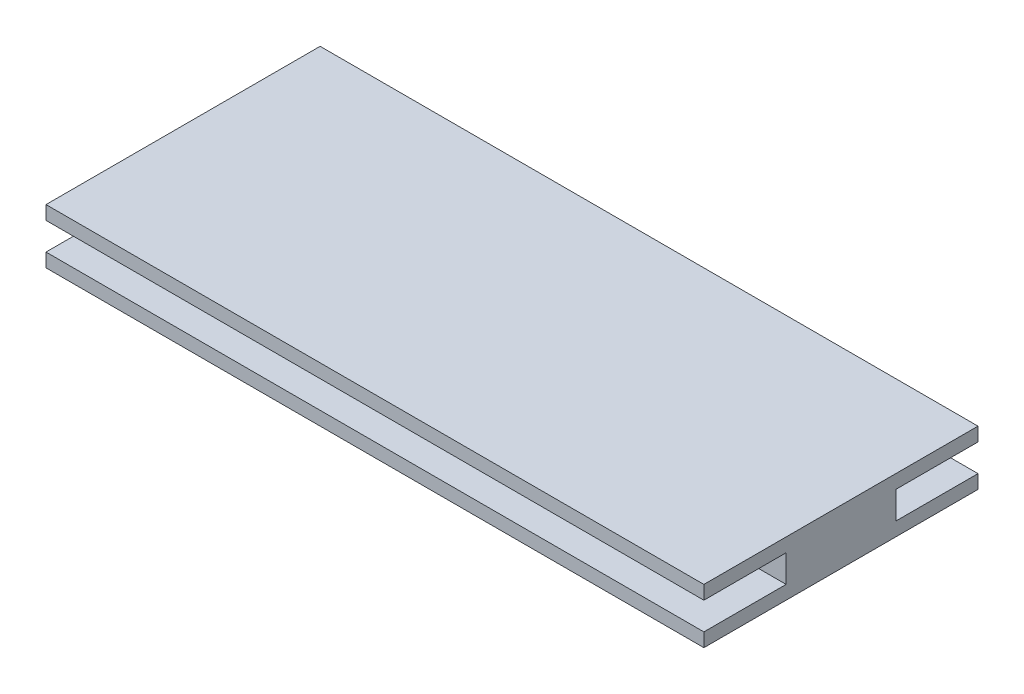
SolidWorks part; units mm, degrees
ref_plane "Front Plane" through (0, 0, 0) normal (0, 0, 1) x (1, 0, 0)
ref_plane "Top Plane" through (0, 0, 0) normal (0, 1, 0) x (1, 0, 0)
ref_plane "Right Plane" through (0, 0, 0) normal (1, 0, 0) x (0, 0, -1)
other "Bounding Box"
ref_plane "Default Plane" through (0, 3.175, -15.875) normal (0, 0, 1) x (1, 0, 0)
sketch "Sketch1" plane through (0, 0, 0) normal (1, 0, 0) x (0, 0, -1)
  line L0 (-15.875, 1.5875) -> (-15.875, 3.175)
  line L1 (-15.875, -3.175) -> (15.875, -3.175)
  line L2 (-15.875, -3.175) -> (-15.875, -1.5875)
  line L3 (-15.875, 3.175) -> (15.875, 3.175)
  line L4 (15.875, -3.175) -> (15.875, -1.5875)
  line L5 (-15.875, -3.175) -> (15.875, 3.175) construction
  line L6 (-15.875, 3.175) -> (15.875, -3.175) construction
  line L7 (15.875, 1.5875) -> (15.875, 3.175)
  line L14 (6.35, -1.5875) -> (6.35, 1.5875)
  line L15 (-6.35, -1.5875) -> (-6.35, 1.5875)
  line L16 (6.35, 1.5875) -> (15.875, 1.5875)
  line L17 (-6.35, 1.5875) -> (-15.875, 1.5875)
  line L18 (-6.35, -1.5875) -> (-15.875, -1.5875)
  line L19 (6.35, -1.5875) -> (15.875, -1.5875)
  point P0 (0, 0)
  dimension "D1" = 31.75
  dimension "D2" = 6.35
  dimension "D7" = 3.175
  dimension "D8" = 3.175
extrude "Boss-Extrude1" add sketch "Sketch1" along normal blind 76.2
